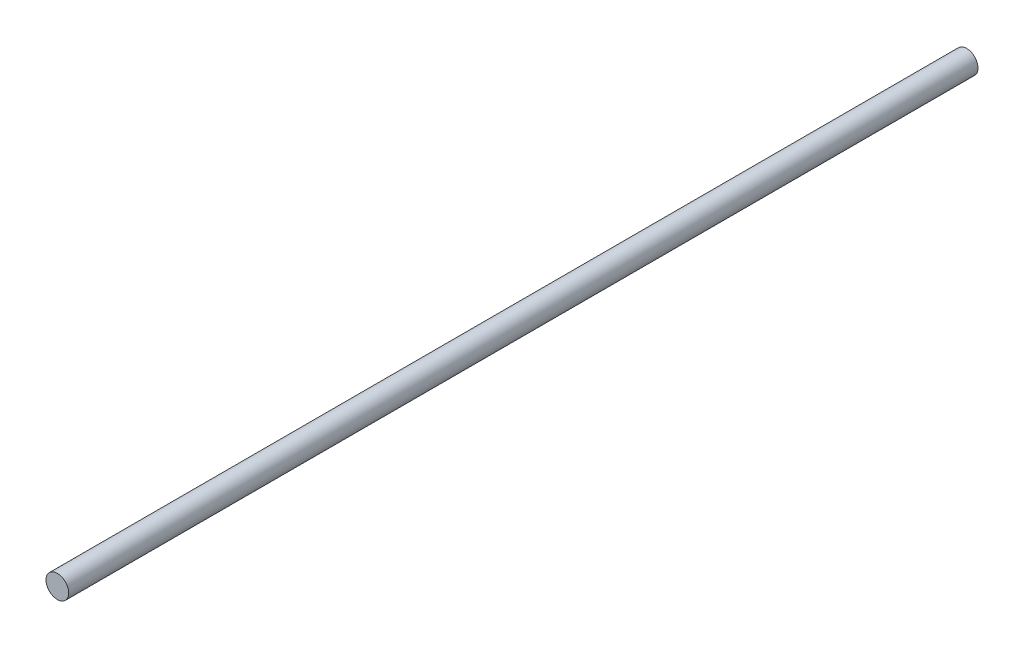
SolidWorks part; units mm, degrees
material "Pine"
ref_plane "Front Plane" through (0, 0, 0) normal (0, 0, 1) x (1, 0, 0)
ref_plane "Top Plane" through (0, 0, 0) normal (0, 1, 0) x (1, 0, 0)
ref_plane "Right Plane" through (0, 0, 0) normal (1, 0, 0) x (0, 0, -1)
sketch "Sketch1" plane through (0, 0, 0) normal (0, 0, 1) x (1, 0, 0)
  circle A0 centre (0, 0) radius 3.175
  dimension "D1" = 6.35
extrude "Boss-Extrude1" add sketch "Sketch1" along normal mid plane 254
